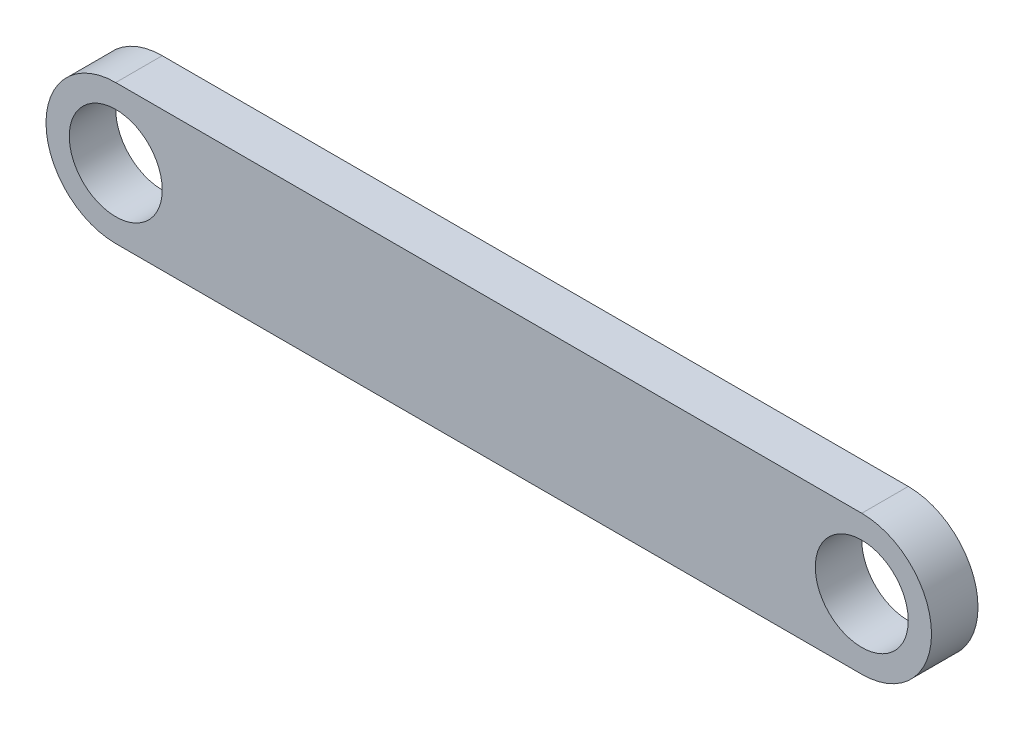
SolidWorks part; units mm, degrees
ref_plane "Front Plane" through (0, 0, 0) normal (0, 0, 1) x (1, 0, 0)
ref_plane "Top Plane" through (0, 0, 0) normal (0, 1, 0) x (1, 0, 0)
ref_plane "Right Plane" through (0, 0, 0) normal (1, 0, 0) x (0, 0, -1)
sketch "Sketch1" plane through (0, 0, 0) normal (0, 0, 1) x (1, 0, 0)
  line L0 (0, 0) -> (-16.0465, 0) construction
  line L1 (0, -1.5) -> (-16.0465, -1.5)
  line L2 (0, 1.5) -> (-16.0465, 1.5)
  arc A0 (0, -1.5) -> (0, 1.5) centre (0, 0) ccw
  arc A1 (-16.0465, 1.5) -> (-16.0465, -1.5) centre (-16.0465, 0) ccw
  circle A2 centre (-16.0465, 0) radius 1
  circle A3 centre (0, 0) radius 1
  point P3 (-8.0233, 0)
  dimension "D2" = 1.5
  dimension "D3" = 2
  dimension "D1" = 16.0465
extrude "Boss-Extrude1" add sketch "Sketch1" along normal mid plane 1
